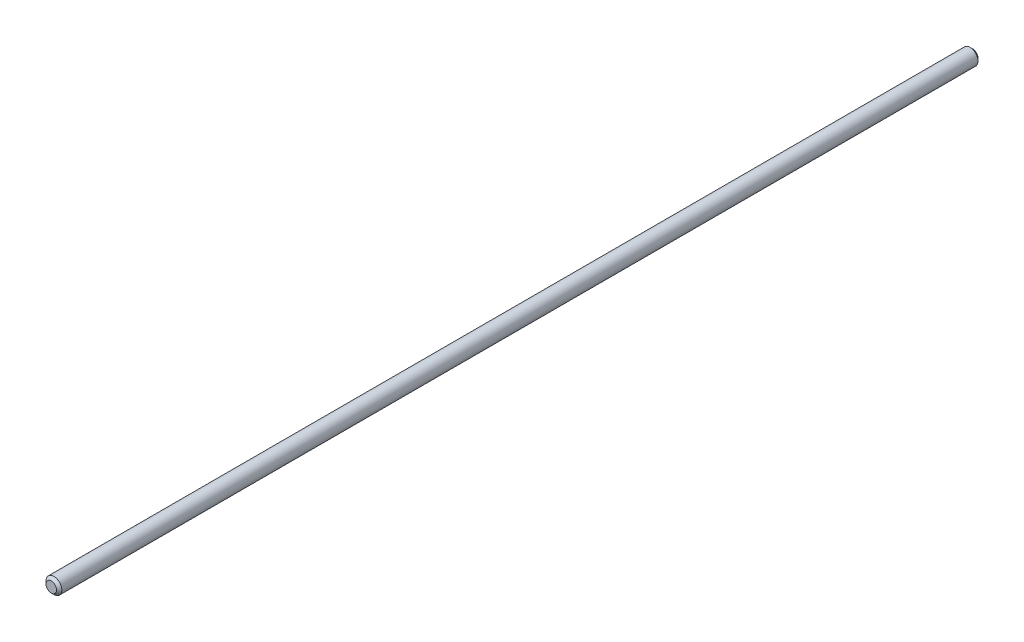
SolidWorks part; units mm, degrees
material "AISI 1020"
ref_plane "Спереди" through (0, 0, 0) normal (0, 0, 1) x (1, 0, 0)
ref_plane "Сверху" through (0, 0, 0) normal (0, 1, 0) x (1, 0, 0)
ref_plane "Справа" through (0, 0, 0) normal (1, 0, 0) x (0, 0, -1)
sketch "Эскиз1" plane through (0, 0, 0) normal (0, 0, 1) x (1, 0, 0)
  circle A0 centre (0, 0) radius 1.5
  dimension "D1" = 3
extrude "Бобышка-Вытянуть1" add sketch "Эскиз1" along normal blind 175
chamfer "Фаска1" distance 0.5 angle 45 2 edges at (1.5, 0, 0) (1.5, 0, 175)
